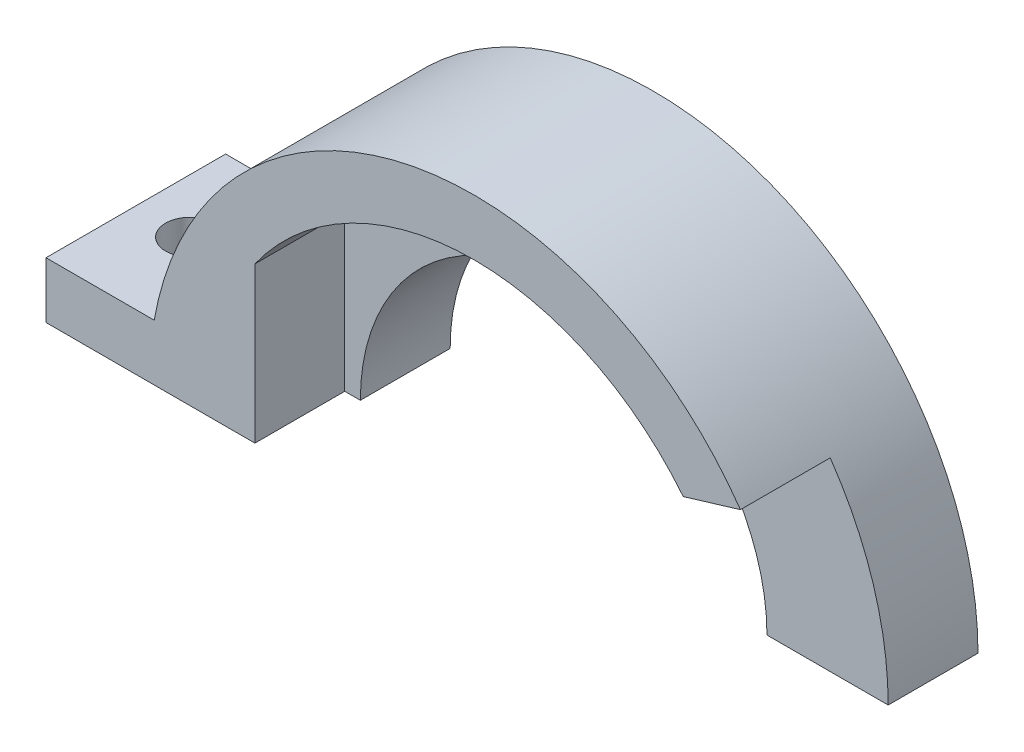
SolidWorks part; units mm, degrees
ref_plane "Front Plane" through (0, 0, 0) normal (0, 0, 1) x (1, 0, 0)
ref_plane "Top Plane" through (0, 0, 0) normal (0, 1, 0) x (1, 0, 0)
ref_plane "Right Plane" through (0, 0, 0) normal (1, 0, 0) x (0, 0, -1)
sketch "Sketch1" plane through (0, 0, 0) normal (0, 0, 1) x (1, 0, 0)
  line L1 (-19.5, 13.8306) -> (-19.5, 0)
  line L2 (-28.9068, 0) -> (-19.5, 0)
  line L3 (23.9068, 0) -> (28.9068, 0)
  arc A0 (23.9068, 0) -> (-19.5, 13.8306) centre (0, 0) ccw
  arc A1 (28.9068, 0) -> (-28.9068, 0) centre (0, 0) ccw
  dimension "D1" = 47.8136
  dimension "D2" = 5
  dimension "D3" = 19.5
extrude "Boss-Extrude1" add sketch "Sketch1" along normal blind 8
sketch "Sketch2" plane through (0, 0, 8) normal (0, 0, 1) x (1, 0, 0)
  line L0 (-28.9068, 0) -> (-18.1106, 0)
  line L1 (18.1106, 0) -> (28.9068, 0)
  arc A0 (18.1106, 0) -> (-18.1106, 0) centre (0, 0) ccw
  arc A1 (28.9068, 0) -> (-28.9068, 0) centre (0, 0) ccw
  dimension "D1" = 36.2211
sketch "Sketch5" plane through (0, 0, 0) normal (0, 0, -1) x (-1, 0, 0)
  line L0 (0, 0) -> (-18.6509, 14.9559)
  line L2 (-58.1332, -8.3123) -> (0, 0)
  line L3 (28.9068, 0) -> (19.5, 0) construction
  line L8 (-18.6509, 14.9559) -> (-43.5038, 22.4424)
  line L9 (-43.5038, 22.4424) -> (-58.1332, -8.3123)
  arc A1 (19.5, 13.8306) -> (-23.9068, 0) centre (0, 0) ccw construction
  dimension "D1" = 141.274
extrude "Cut-Extrude2" cut sketch "Sketch5" against normal blind 8
sketch "Sketch6" plane through (0, 0, 0) normal (0, 0, -1) x (-1, 0, 0)
  line L0 (-28.9068, 0) -> (-18.1106, 0)
  line L1 (18.1106, 0) -> (28.9068, 0)
  arc A0 (18.1106, 0) -> (-18.1106, 0) centre (0, 0) ccw
  arc A1 (28.9068, 0) -> (-28.9068, 0) centre (0, 0) ccw
extrude "Boss-Extrude2" add sketch "Sketch6" along normal blind 8
sketch "Sketch7" plane through (0, 0, -8) normal (0, 0, -1) x (-1, 0, 0)
  line L5 (28.9068, 0) -> (38.1106, 0)
  line L7 (28.4711, 5) -> (38.1106, 5)
  line L8 (38.1106, 0) -> (38.1106, 5)
  arc A0 (28.9068, 0) -> (28.4711, 5) centre (0, 0) ccw
  dimension "D2" = 5
extrude "Boss-Extrude3" add sketch "Sketch7" against normal through all
sketch "Sketch8" plane through (0, 5, 0) normal (0, 1, 0) x (1, 0, 0)
  line L0 (-38.1106, -8) -> (-28.4711, -8) construction
  line L1 (-38.1106, 8) -> (-28.4711, 8) construction
  line L2 (-38.1106, 8) -> (-38.1106, -8) construction
  line L3 (-38.1106, -8) -> (-28.4711, -8) construction
  line L4 (-28.4711, 8) -> (-28.4711, -8) construction
  line L5 (-38.1106, 8) -> (-28.4711, -8) construction
  line L6 (-38.1106, -8) -> (-28.4711, 8) construction
  line L7 (-38.1106, 8) -> (-28.4711, 8) construction
  line L8 (-28.4711, -8) -> (-28.4711, 8) construction
  line L9 (-38.1106, -8) -> (-38.1106, 8) construction
  circle A0 centre (-33.2908, 0) radius 2.165
  point P0 (-33.2908, 0)
extrude "Cut-Extrude3" cut sketch "Sketch8" against normal through all
